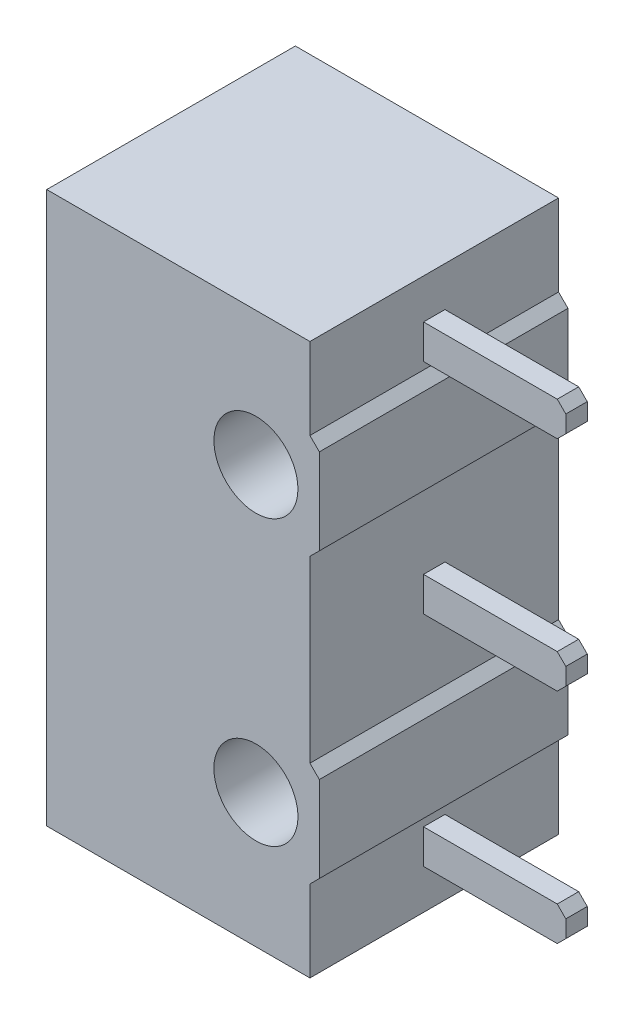
SolidWorks part; units mm, degrees
ref_plane "前视基准面" through (0, 0, 0) normal (0, 0, 1) x (1, 0, 0)
ref_plane "上视基准面" through (0, 0, 0) normal (0, 1, 0) x (1, 0, 0)
ref_plane "右视基准面" through (0, 0, 0) normal (1, 0, 0) x (0, 0, -1)
sketch "草图1" plane through (0, 0, 0) normal (0, 0, 1) x (1, 0, 0)
  line L0 (0, 6.43) -> (6.14, 6.43) construction
  line L1 (0, 0) -> (6.14, 0)
  line L2 (0, 0) -> (0, 12.86)
  line L3 (0, 12.86) -> (6.14, 12.86)
  line L4 (6.14, 0) -> (6.14, 12.86) construction
  line L5 (6.36, 10.74) -> (6.36, 8.74)
  line L6 (3.9, 9.74) -> (5.86, 9.74) construction
  line L7 (6.36, 10.74) -> (6.14, 10.96)
  line L8 (6.14, 12.86) -> (6.14, 10.96)
  line L9 (6.36, 8.74) -> (6.14, 8.52)
  line L10 (6.14, 8.52) -> (6.14, 4.34)
  line L11 (6.36, 4.12) -> (6.14, 4.34)
  line L12 (6.36, 2.12) -> (6.36, 4.12)
  line L13 (6.36, 2.12) -> (6.14, 1.9)
  line L14 (6.14, 0) -> (6.14, 1.9)
  circle A0 centre (4.88, 9.74) radius 0.98
  circle A1 centre (4.88, 3.12) radius 0.98
  dimension "D3" = 1.96
  dimension "D4" = 6.62
  dimension "D1" = 6.14
  dimension "D2" = 12.86
  dimension "D5" = 4.88
  dimension "D6" = 1.48
  dimension "D7" = 2
  dimension "D8" = 135
extrude "凸台-拉伸1" add sketch "草图1" along normal blind 5.8
sketch "草图2" plane through (6.14, 0, 0) normal (1, 0, 0) x (0, 0, -1)
  line L0 (-2.9, 12.86) -> (-2.9, 0) construction
  line L1 (-5.8, 12.86) -> (0, 12.86) construction
  line L2 (-5.8, 0) -> (0, 0) construction
  line L3 (-5.8, 6.43) -> (0, 6.43) construction
  line L4 (-3.15, 11.93) -> (-2.65, 11.93)
  line L5 (-3.15, 11.93) -> (-3.15, 11.13)
  line L6 (-3.15, 11.13) -> (-2.65, 11.13)
  line L7 (-2.65, 11.93) -> (-2.65, 11.13)
  line L8 (-5.8, 4.34) -> (-5.8, 8.52) construction
  line L9 (0, 4.34) -> (0, 8.52) construction
  line L10 (-3.15, 1.73) -> (-2.65, 1.73)
  line L11 (-3.15, 0.93) -> (-3.15, 1.73)
  line L12 (-3.15, 0.93) -> (-2.65, 0.93)
  line L13 (-2.65, 0.93) -> (-2.65, 1.73)
  line L15 (-3.15, 6.83) -> (-2.65, 6.83)
  line L16 (-3.15, 6.83) -> (-3.15, 6.03)
  line L17 (-3.15, 6.03) -> (-2.65, 6.03)
  line L18 (-2.65, 6.83) -> (-2.65, 6.03)
  point P20 (-2.9, 11.93)
  dimension "D1" = 0.8
  dimension "D2" = 0.5
  dimension "D3" = 11
extrude "凸台-拉伸2" add sketch "草图2" along normal blind 3.32
chamfer "倒角2" distance 0.2 angle 45 6 edges at (9.46, 0.93, 2.9) (9.46, 1.73, 2.9) (9.46, 6.03, 2.9) (9.46, 6.83, 2.9) (9.46, 11.13, 2.9) (9.46, 11.93, 2.9)
ref_plane "基准面1" through (0, 0, 2.9) normal (0, 0, 1) x (1, 0, 0)
sketch "草图3" plane through (0, 0, 2.9) normal (0, 0, 1) x (1, 0, 0)
  line L0 (0, 4.8) -> (-0.5, 4.8)
  line L1 (0, 12.86) -> (0, 0) construction
  line L2 (0, 3.8) -> (-0.5, 3.8)
  line L3 (0, 4.3) -> (6.36, 4.3) construction
  line L4 (6.36, 2.12) -> (6.36, 4.12) construction
  line L5 (0, 0) -> (6.14, 0) construction
  line L6 (0, 12.86) -> (0, 0) construction
  line L7 (0, 4.8) -> (0, 3.8)
  arc A0 (-0.5, 4.8) -> (-0.5, 3.8) centre (-0.5, 4.3) ccw
  dimension "D3" = 0.5
  dimension "D1" = 4.3
  dimension "D2" = 1
extrude "凸台-拉伸3" add sketch "草图3" along normal blind 1.38 and the other way blind 1.38
sketch "草图4" plane through (0, 0, 2.9) normal (0, 0, 1) x (1, 0, 0)
  line L0 (0, 12.86) -> (0, 0) construction
  line L1 (0, 0) -> (6.14, 0) construction
  circle A0 centre (0, 1.93) radius 0.25
  dimension "D1" = 0.5
  dimension "D2" = 1.93
extrude "凸台-拉伸4" add sketch "草图4" along normal blind 0.2 and the other way blind 0.2
